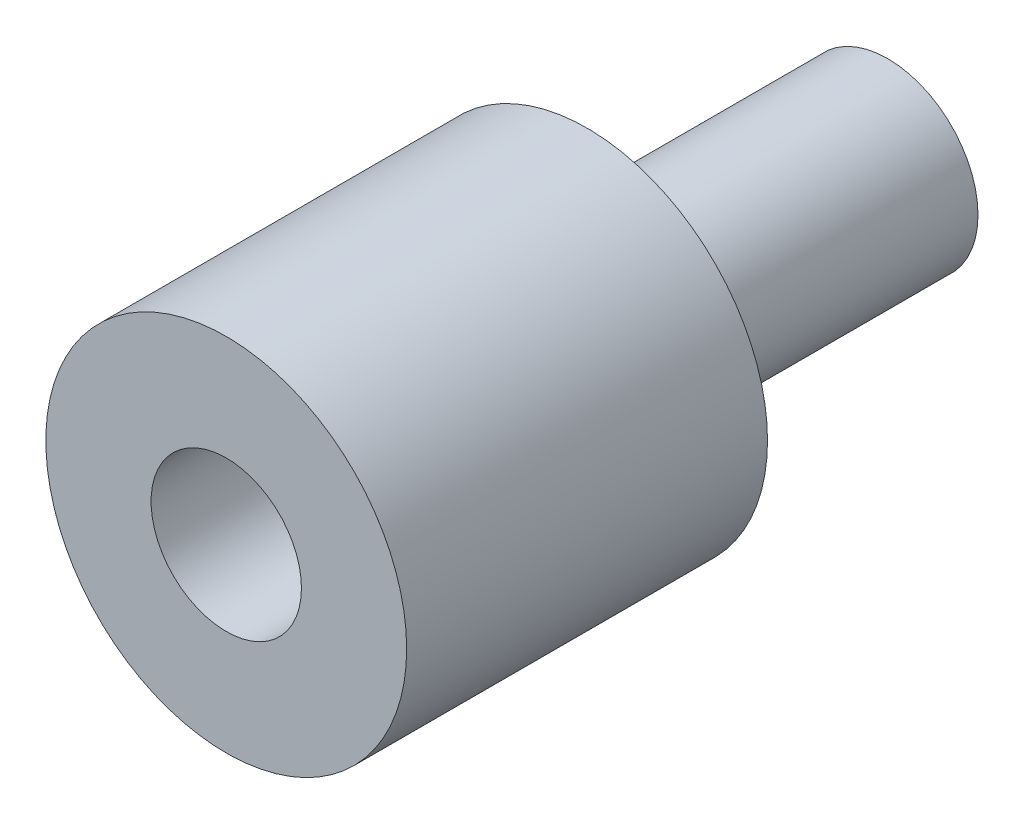
SolidWorks part; units mm, degrees
ref_plane "Front Plane" through (0, 0, 0) normal (0, 0, 1) x (1, 0, 0)
ref_plane "Top Plane" through (0, 0, 0) normal (0, 1, 0) x (1, 0, 0)
ref_plane "Right Plane" through (0, 0, 0) normal (1, 0, 0) x (0, 0, -1)
sketch "Sketch1" plane through (0, 0, 0) normal (0, 0, 1) x (1, 0, 0)
  circle A0 centre (0, 0) radius 12
extrude "Boss-Extrude1" add sketch "Sketch1" along normal blind 24
sketch "Sketch2" plane through (0, 0, 24) normal (0, 0, 1) x (1, 0, 0)
  circle A0 centre (0, 0) radius 5
extrude "Cut-Extrude1" cut sketch "Sketch2" against normal blind 12
sketch "Sketch3" plane through (0, 0, 0) normal (0, 0, -1) x (-1, 0, 0)
  circle A0 centre (0, 0) radius 6
extrude "Boss-Extrude2" add sketch "Sketch3" along normal blind 20
